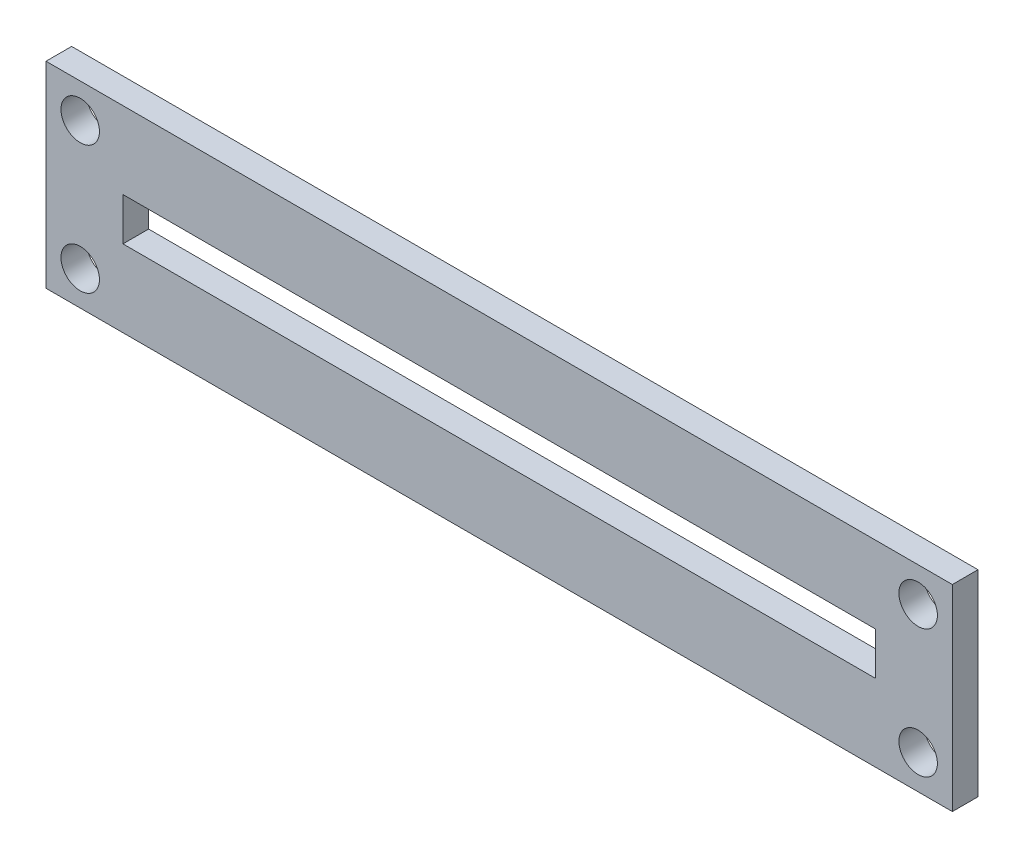
SolidWorks part; units mm, degrees
ref_plane "Front Plane" through (0, 0, 0) normal (0, 0, 1) x (1, 0, 0)
ref_plane "Top Plane" through (0, 0, 0) normal (0, 1, 0) x (1, 0, 0)
ref_plane "Right Plane" through (0, 0, 0) normal (1, 0, 0) x (0, 0, -1)
sketch "Sketch1" plane through (0, 0, 0) normal (0, 0, 1) x (1, 0, 0)
  line L0 (-53, 11.5) -> (53, -11.5) construction
  line L1 (-53, 11.5) -> (53, 11.5)
  line L2 (-53, 11.5) -> (-53, -11.5)
  line L3 (-53, -11.5) -> (53, -11.5)
  line L4 (53, 11.5) -> (53, -11.5)
  line L5 (53, 11.5) -> (-53, -11.5) construction
  line L10 (-49, 7.5) -> (-49, -7.5) construction
  line L11 (-44, 2.5) -> (-44, -2.5)
  line L12 (-44, -2.5) -> (44, -2.5)
  line L13 (44, 2.5) -> (44, -2.5)
  line L14 (-44, 2.5) -> (44, 2.5)
  circle A0 centre (-49, 7.5) radius 2.25
  circle A1 centre (-49, -7.5) radius 2.25
  circle A2 centre (49, 7.5) radius 2.25
  circle A3 centre (49, -7.5) radius 2.25
  point P4 (0, 0)
  dimension "D4" = 4.5
  dimension "D5" = 15
  dimension "D6" = 4
  dimension "D7" = 4
  dimension "D3" = 98
  dimension "D1" = 23
  dimension "D2" = 106
  dimension "D9" = 9
  dimension "D8" = 2
extrude "Boss-Extrude1" add sketch "Sketch1" along normal blind 3
